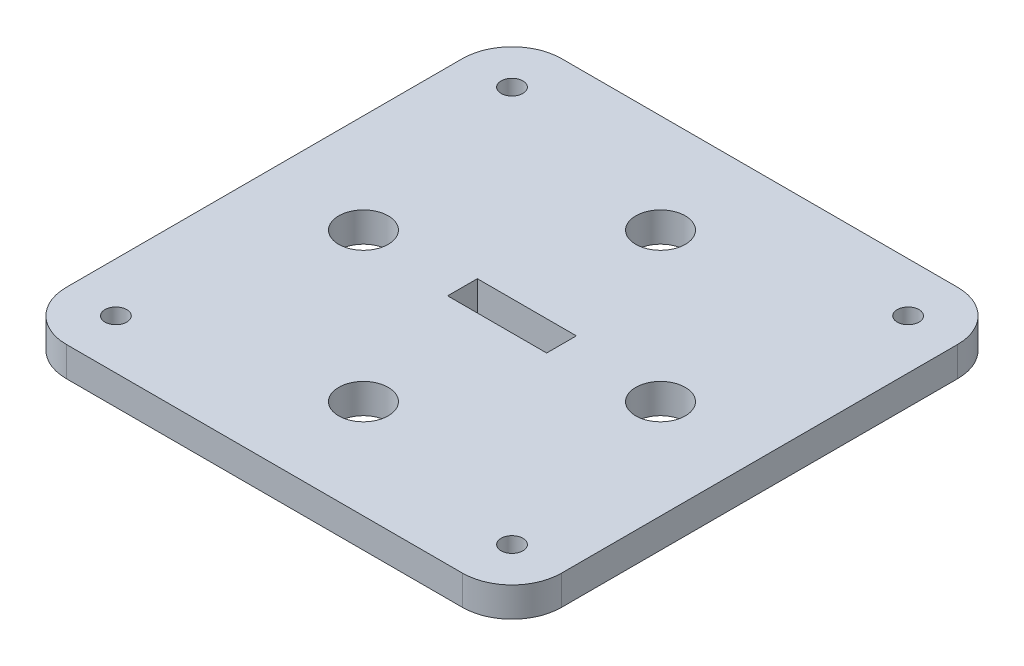
SolidWorks part; units mm, degrees
ref_plane "Front Plane" through (0, 0, 0) normal (0, 0, 1) x (1, 0, 0)
ref_plane "Top Plane" through (0, 0, 0) normal (0, 1, 0) x (1, 0, 0)
ref_plane "Right Plane" through (0, 0, 0) normal (1, 0, 0) x (0, 0, -1)
sketch "Sketch1" plane through (0, 0, 0) normal (0, 1, 0) x (1, 0, 0)
  line L0 (0, 25) -> (0, -25) construction
  line L1 (-25, -25) -> (25, -25)
  line L2 (-25, -25) -> (-25, 25)
  line L3 (-25, 25) -> (25, 25)
  line L4 (25, -25) -> (25, 25)
  line L5 (-25, -25) -> (25, 25) construction
  line L6 (-25, 25) -> (25, -25) construction
  line L7 (-25, 0) -> (25, 0) construction
  line L8 (-5, -1.5) -> (5, -1.5)
  line L9 (-5, -1.5) -> (-5, 1.5)
  line L10 (-5, 1.5) -> (5, 1.5)
  line L11 (5, -1.5) -> (5, 1.5)
  line L12 (-5, -1.5) -> (5, 1.5) construction
  line L13 (-5, 1.5) -> (5, -1.5) construction
  circle A0 centre (-15, 0) radius 2.5
  circle A2 centre (15, 0) radius 2.5
  circle A3 centre (-20, 20) radius 1.1
  circle A4 centre (20, 20) radius 1.1
  circle A5 centre (20, -20) radius 1.1
  circle A6 centre (-20, -20) radius 1.1
  circle A7 centre (0, 15) radius 2.5
  circle A8 centre (0, -15) radius 2.5
  point P0 (0, 0)
  point P13 (0, 0)
  dimension "D3" = 15
  dimension "D4" = 5
  dimension "D7" = 2.2
  dimension "D10" = 5
  dimension "D1" = 50
  dimension "D2" = 50
  dimension "D5" = 10
  dimension "D6" = 3
  dimension "D8" = 5
  dimension "D9" = 5
  dimension "D11" = 15
extrude "Boss-Extrude1" add sketch "Sketch1" along normal blind 3
fillet "Fillet1" radius 5 4 edges at (25, 1.5, -25) (-25, 1.5, -25) (-25, 1.5, 25) (25, 1.5, 25)
